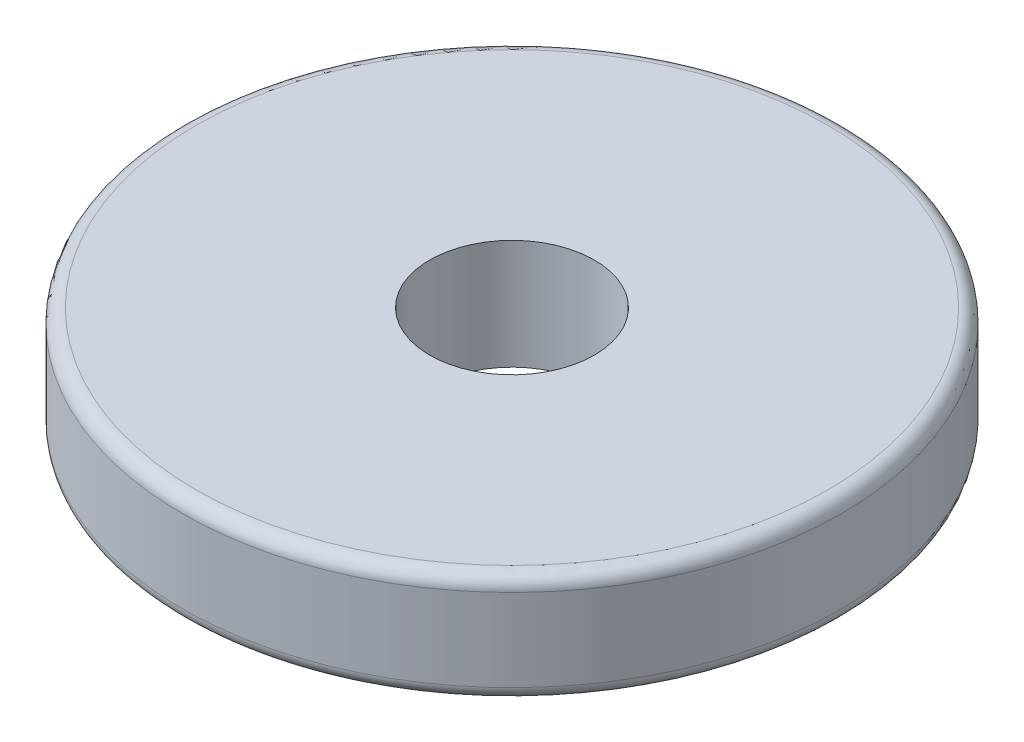
SolidWorks part; units mm, degrees
ref_plane "前视基准面" through (0, 0, 0) normal (0, 0, 1) x (1, 0, 0)
ref_plane "上视基准面" through (0, 0, 0) normal (0, 1, 0) x (1, 0, 0)
ref_plane "右视基准面" through (0, 0, 0) normal (1, 0, 0) x (0, 0, -1)
other "Configuration Table"
sketch "草图1" plane through (0, 0, 0) normal (0, 0, 1) x (1, 0, 0)
  line L0 (0, -346.4166) -> (0, 16974.411) construction
  line L1 (7.5, 3.75) -> (30, 3.75) construction
  line L2 (7.5, 5) -> (30, 5) construction
  line L3 (7.5, 5) -> (7.5, -5)
  line L4 (7.5, -5) -> (30, -5) construction
  line L5 (30, 5) -> (30, -5) construction
  line L6 (7.5, -3.75) -> (30, -3.75) construction
  line L7 (28.75, 5) -> (28.75, -5) construction
  line L8 (7.5, -5) -> (28.75, -5)
  line L9 (30, -3.75) -> (30, 3.75)
  line L10 (28.75, 5) -> (7.5, 5)
  line L11 (28.5, 3.5) -> (9, 3.5)
  line L12 (9, 3.5) -> (9, -3.5)
  line L13 (9, -3.5) -> (28.5, -3.5)
  line L14 (28.5, -3.5) -> (28.5, 3.5)
  arc A0 (30, 3.75) -> (28.75, 5) centre (28.75, 3.75) ccw
  arc A1 (28.75, -5) -> (30, -3.75) centre (28.75, -3.75) ccw
  arc A2 (28.5, -3.5) -> (28.5, -3.5) centre (28.5, -3.5) ccw
  arc A3 (28.5, 3.5) -> (28.5, 3.5) centre (28.5, 3.5) ccw
  point P7 (7.5, 0)
  dimension "D1" = 30
  dimension "D2" = 7.5
  dimension "D3" = 10
  dimension "D4" = 1.25
  dimension "D5" = 1.25
  dimension "D6" = 1.25
  dimension "D7" = 1.5
revolve "旋转3" add sketch "草图1" angle 360 about L0
